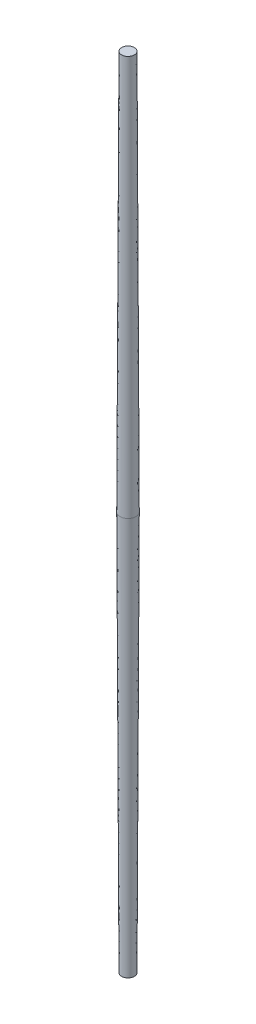
SolidWorks part; units mm, degrees
ref_plane "Plan de face" through (0, 0, 0) normal (0, 0, 1) x (1, 0, 0)
ref_plane "Plan de dessus" through (0, 0, 0) normal (0, 1, 0) x (1, 0, 0)
ref_plane "Plan de droite" through (0, 0, 0) normal (1, 0, 0) x (0, 0, -1)
sketch "Esquisse1" plane through (0, 0, 0) normal (0, 0, 1) x (1, 0, 0)
  line L0 (0, 0) -> (5, 0)
  line L1 (5, 0) -> (4, 250)
  line L2 (4, 250) -> (0, 250)
  line L3 (0, 250) -> (0, 0)
  dimension "D1" = 250
  dimension "D2" = 5
  dimension "D3" = 4
revolve "Révolution1" add sketch "Esquisse1" angle 360 about L3
mirror "Symétrie1" about plane through (0, 0, 0) normal (0, 1, 0) of "Révolution1"
